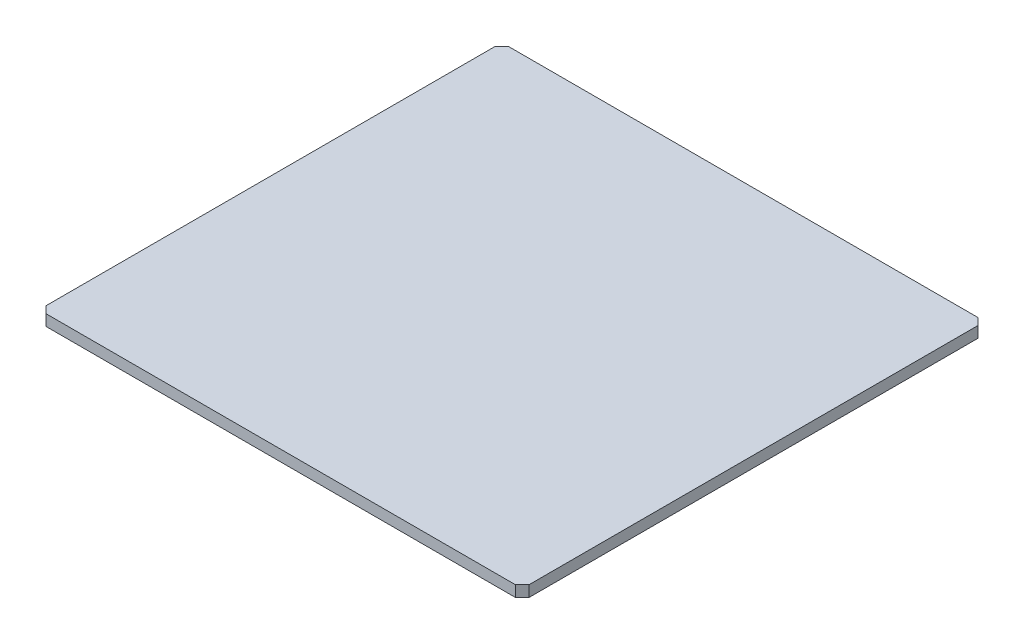
SolidWorks part; units mm, degrees
ref_plane "Front Plane" through (0, 0, 0) normal (0, 0, 1) x (1, 0, 0)
ref_plane "Top Plane" through (0, 0, 0) normal (0, 1, 0) x (1, 0, 0)
ref_plane "Right Plane" through (0, 0, 0) normal (1, 0, 0) x (0, 0, -1)
sketch "Sketch1" plane through (0, 0, 0) normal (0, 1, 0) x (1, 0, 0)
  line L0 (0.1017, 94.1375) -> (1.5263, 95.5621)
  line L1 (0.1017, -0.0104) -> (99.8983, -0.0104) construction
  line L2 (0.1017, -0.0104) -> (0.1017, 95.5621) construction
  line L3 (0.1017, 95.5621) -> (99.8983, 95.5621) construction
  line L4 (99.8983, -0.0104) -> (99.8983, 95.5621) construction
  line L5 (1.5263, 95.5621) -> (98.4737, 95.5621)
  line L6 (98.4737, 95.5621) -> (99.8983, 94.1375)
  line L7 (99.8983, 94.1375) -> (99.8983, 1.4142)
  line L8 (99.8983, 1.4142) -> (98.4737, -0.0104)
  line L9 (98.4737, -0.0104) -> (1.5263, -0.0104)
  line L10 (1.5263, -0.0104) -> (0.1017, 1.4142)
  line L11 (0.1017, 1.4142) -> (0.1017, 94.1375)
extrude "Boss-Extrude1" add sketch "Sketch1" along normal blind 2.286
ref_plane "center-of-slot" through (0, 1.143, 0) normal (0, 1, 0) x (1, 0, 0)
ref_plane "center-of-module" through (50, 0, 0) normal (1, 0, 0) x (0, 0, -1)
